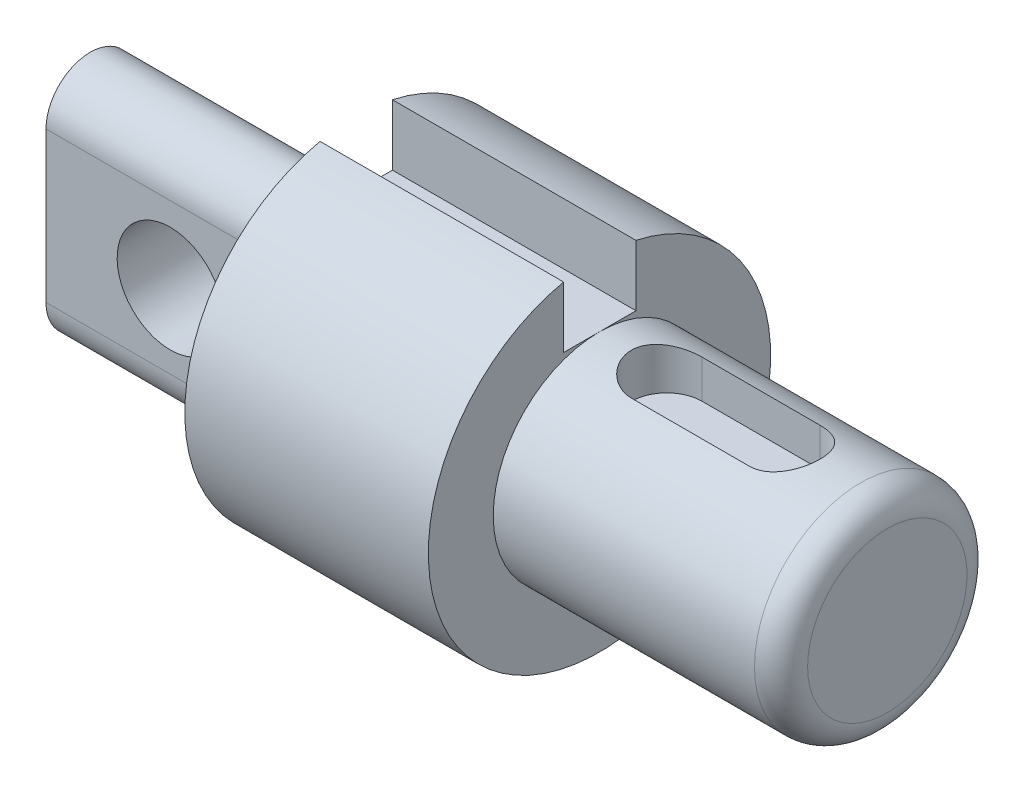
SolidWorks part; units mm, degrees
ref_plane "Front Plane" through (0, 0, 0) normal (0, 0, 1) x (1, 0, 0)
ref_plane "Top Plane" through (0, 0, 0) normal (0, 1, 0) x (1, 0, 0)
ref_plane "Right Plane" through (0, 0, 0) normal (1, 0, 0) x (0, 0, -1)
sketch "Sketch1" plane through (0, 0, 0) normal (0, 0, 1) x (1, 0, 0)
  line L1 (0, 0) -> (0, 14.6569)
  line L2 (0, 14.6569) -> (55, 14.6569)
  line L3 (55, 14.6569) -> (55, 0)
  line L4 (55, 0) -> (120, 0)
  line L5 (120, 0) -> (120, -24)
  line L6 (120, -24) -> (0, -24)
  line L8 (0, -24) -> (0, 0)
  line L9 (-5.2816, -24) -> (149.0033, -24) construction
  dimension "D1" = 65
  dimension "D2" = 55
  dimension "D3" = 24
revolve "Revolve1" add sketch "Sketch1" angle 360 about L9
fillet "Fillet1" radius 6 1 edges at (120, -24, 24)
sketch "Sketch2" plane through (0, 0, 0) normal (0, 1, 0) x (1, 0, 0)
  line L0 (70.1954, 0) -> (96.8123, 0) construction
  line L1 (70.1954, 8) -> (96.8123, 8)
  line L2 (70.1954, -8) -> (96.8123, -8)
  arc A0 (70.1954, 8) -> (70.1954, -8) centre (70.1954, 0) ccw
  arc A1 (96.8123, -8) -> (96.8123, 8) centre (96.8123, 0) ccw
  point P3 (83.5038, 0)
  point P13 (0, 6.771)
  point P14 (0, 0)
  point P17 (0, 0)
  point P22 (0, 0)
  point P23 (0, 0)
  point P24 (0, 0)
  point P25 (0, 0)
  point P26 (0, 0)
  point P27 (0, 0)
  dimension "D1" = 16
extrude "Cut-Extrude8" cut sketch "Sketch2" against normal blind 10
sketch "Sketch6" plane through (0, 0, 0) normal (0, 1, 0) x (1, 0, 0)
  line L0 (55, -24) -> (55, 24) construction
  line L1 (0, 8.2367) -> (55, 8.2367)
  line L2 (0, 8.2367) -> (0, -8.107)
  line L3 (0, -8.107) -> (55, -8.107)
  line L4 (55, 8.2367) -> (55, -8.107)
  line L5 (0, 8.2367) -> (55, -8.107) construction
  line L6 (0, -8.107) -> (55, 8.2367) construction
  line L7 (0, 38.6569) -> (0, -38.6569) construction
  point P0 (27.5, 0.0649)
  point P7 (0, -8.107)
extrude "Cut-Extrude15" cut sketch "Sketch6" along normal blind 20
sketch "Sketch7" plane through (0, 0, 0) normal (0, 1, 0) x (1, 0, 0)
  circle A0 centre (27.9643, 0) radius 5.1986
  point P2 (27.9643, 0)
extrude "Cut-Extrude16" cut sketch "Sketch7" against normal blind 10
sketch "Sketch8" plane through (0, 0, 0) normal (-1, 0, 0) x (0, 0, 1)
  line L0 (0, -12.8221) -> (0, -46.7571) construction
  line L3 (10, -12.8221) -> (10, -46.7571)
  line L4 (-10, -12.8221) -> (-10, -46.7571)
  arc A2 (10, -12.8221) -> (-10, -12.8221) centre (0, -12.8221) ccw
  arc A3 (-10, -46.7571) -> (10, -46.7571) centre (0, -46.7571) ccw
  point P2 (0, -29.7896)
  dimension "D1" = 20
extrude "Boss-Extrude1" add sketch "Sketch8" along normal blind 60
sketch "Sketch9" plane through (0, 0, -10) normal (0, 0, -1) x (-1, 0, 0)
  circle A0 centre (31.9336, -30.0142) radius 12
  point P2 (31.9336, -30.0142)
  dimension "D1" = 24
extrude "Cut-Extrude17" cut sketch "Sketch9" against normal blind 60
